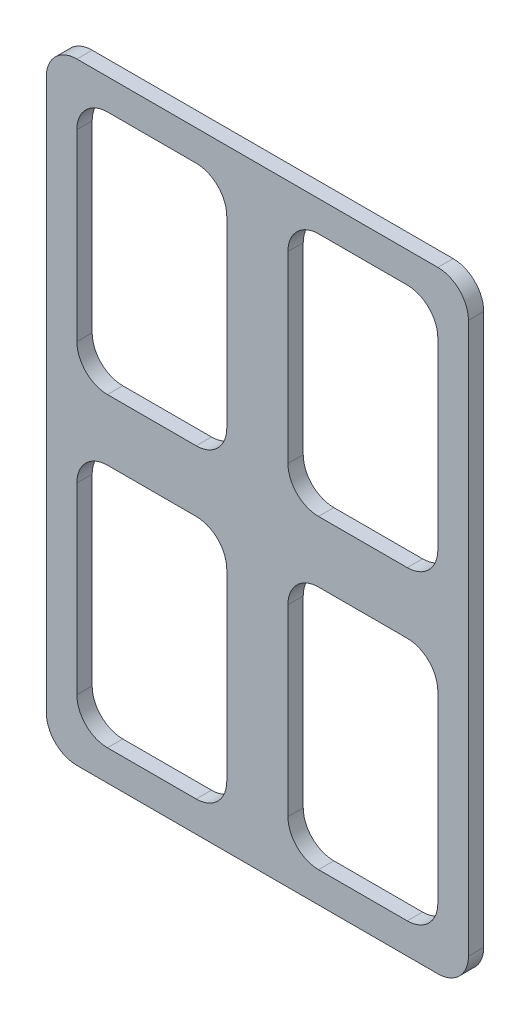
SolidWorks part; units mm, degrees
ref_plane "前视基准面" through (0, 0, 0) normal (0, 0, 1) x (1, 0, 0)
ref_plane "上视基准面" through (0, 0, 0) normal (0, 1, 0) x (1, 0, 0)
ref_plane "右视基准面" through (0, 0, 0) normal (1, 0, 0) x (0, 0, -1)
other "Configuration Table"
sketch "草图1" plane through (0, 0, 0) normal (0, 0, 1) x (1, 0, 0)
  line L0 (0, 171.3642) -> (0, -120.8104) construction
  line L1 (-174.4788, 0) -> (133.182, 0) construction
  line L3 (-69, 100) -> (69, 100)
  line L4 (-69, 100) -> (-69, -100)
  line L5 (-69, -100) -> (69, -100)
  line L6 (69, 100) -> (69, -100)
  dimension "D1" = 138
  dimension "D2" = 200
extrude "凸台-拉伸1" add sketch "草图1" along normal blind 5
sketch "草图2" plane through (0, 0, 5) normal (0, 0, 1) x (1, 0, 0)
  line L0 (0, 105.7025) -> (0, -106.3872) construction
  line L1 (-81.9943, 0) -> (97.9139, 0) construction
  line L4 (69, -100) -> (69, 100) construction
  line L5 (10, 90) -> (59, 90)
  line L6 (10, 90) -> (10, 10)
  line L7 (10, 10) -> (59, 10)
  line L8 (59, 90) -> (59, 10)
  line L9 (69, 100) -> (-69, 100) construction
  line L10 (-10, 10) -> (-59, 10)
  line L11 (-59, 90) -> (-59, 10)
  line L12 (-10, 90) -> (-59, 90)
  line L13 (-10, 90) -> (-10, 10)
  line L14 (10, -10) -> (59, -10)
  line L15 (59, -90) -> (59, -10)
  line L16 (10, -90) -> (59, -90)
  line L17 (10, -90) -> (10, -10)
  line L18 (-10, -90) -> (-10, -10)
  line L19 (-10, -90) -> (-59, -90)
  line L20 (-59, -90) -> (-59, -10)
  line L21 (-10, -10) -> (-59, -10)
  dimension "D1" = 10
  dimension "D2" = 10
  dimension "D3" = 10
  dimension "D4" = 10
extrude "切除-拉伸2" cut sketch "草图2" against normal blind 5
fillet "圆角1" radius 10 20 edges at (-69, -100, 2.5) (69, -100, 2.5) (69, 100, 2.5) (-69, 100, 2.5) (59, -90, 2.5) (10, -90, 2.5) (10, -10, 2.5) (59, -10, 2.5) (-10, -90, 2.5) (-59, -90, 2.5) (-59, -10, 2.5) (-10, -10, 2.5) (-59, 10, 2.5) (-59, 90, 2.5) (-10, 90, 2.5) (-10, 10, 2.5) (59, 10, 2.5) (59, 90, 2.5) (10, 90, 2.5) (10, 10, 2.5)
